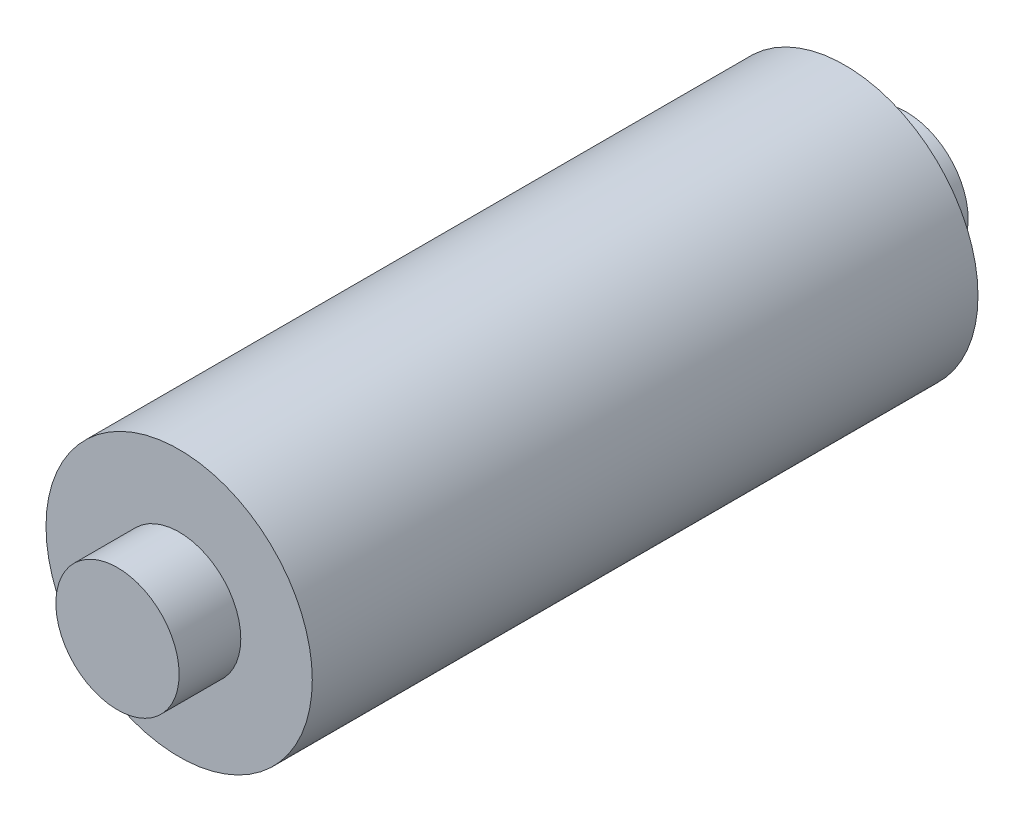
SolidWorks part; units mm, degrees
ref_plane "前视基准面" through (0, 0, 0) normal (0, 0, 1) x (1, 0, 0)
ref_plane "上视基准面" through (0, 0, 0) normal (0, 1, 0) x (1, 0, 0)
ref_plane "右视基准面" through (0, 0, 0) normal (1, 0, 0) x (0, 0, -1)
sketch "草图1" plane through (0, 0, 0) normal (0, 0, 1) x (1, 0, 0)
  circle A0 centre (0, 0) radius 54
  dimension "D1" = 108
extrude "凸台-拉伸1" add sketch "草图1" along normal blind 270
sketch "草图2" plane through (0, 0, 270) normal (0, 0, 1) x (1, 0, 0)
  circle A0 centre (0, 0) radius 25
  dimension "D1" = 50
extrude "凸台-拉伸2" add sketch "草图2" along normal blind 25
sketch "草图3" plane through (0, 0, 0) normal (0, 0, -1) x (-1, 0, 0)
  circle A0 centre (0, 0) radius 25
  dimension "D1" = 50
extrude "凸台-拉伸3" add sketch "草图3" along normal blind 25
